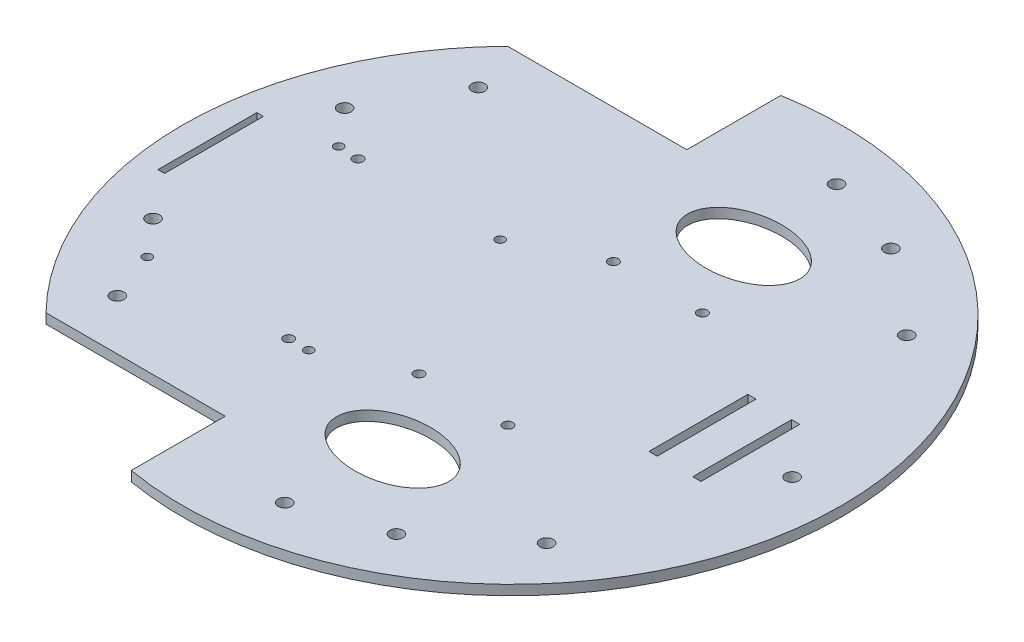
SolidWorks part; units mm, degrees
ref_plane "Спереди" through (0, 0, 0) normal (0, 0, 1) x (1, 0, 0)
ref_plane "Сверху" through (0, 0, 0) normal (0, 1, 0) x (1, 0, 0)
ref_plane "Справа" through (0, 0, 0) normal (1, 0, 0) x (0, 0, -1)
other "Configuration Table"
sketch "Эскиз1" plane through (0, 0, 0) normal (0, 1, 0) x (1, 0, 0)
  circle A0 centre (0, 0) radius 100
extrude "Бобышка-Вытянуть1" add sketch "Эскиз1" along normal blind 3
sketch "Эскиз2" plane through (0, 3, 0) normal (0, 1, 0) x (1, 0, 0)
  circle A1 centre (85, 0) radius 2
  circle A2 centre (65.1138, -54.6369) radius 2
  circle A3 centre (14.7601, -83.7087) radius 2
  circle A4 centre (-42.5, -73.6122) radius 2
  circle A5 centre (-79.8739, -29.0717) radius 2
  circle A6 centre (-79.8739, 29.0717) radius 2
  circle A7 centre (-42.5, 73.6122) radius 2
  circle A8 centre (14.7601, 83.7087) radius 2
  circle A9 centre (65.1138, 54.6369) radius 2
  point P24 (0, 0)
  dimension "D1" = 9
extrude "Вырез-Вытянуть1" cut sketch "Эскиз2" against normal blind 10
sketch "Эскиз4" plane through (0, 3, 0) normal (0, 1, 0) x (1, 0, 0)
  line L0 (-100, 0) -> (100, 0) construction
  line L1 (-52, -87.543) -> (-52, 90.7524) construction
  line L2 (-87, 70.043) -> (-17, 105.043) construction
  line L3 (-87, -105.043) -> (-17, -105.043)
  line L4 (-87, -105.043) -> (-87, -70.043)
  line L5 (-87, -70.043) -> (-17, -70.043)
  line L6 (-17, -105.043) -> (-17, -70.043)
  line L7 (-87, -105.043) -> (-17, -70.043) construction
  line L8 (-87, -70.043) -> (-17, -105.043) construction
  line L9 (-87, 105.043) -> (-17, 70.043) construction
  line L10 (-17, 105.043) -> (-17, 70.043)
  line L11 (-87, 70.043) -> (-17, 70.043)
  line L12 (-87, 105.043) -> (-87, 70.043)
  line L13 (-87, 105.043) -> (-17, 105.043)
  point P5 (-52, 1.6047)
extrude "Вырез-Вытянуть2" cut sketch "Эскиз4" against normal blind 10
sketch "Эскиз5" plane through (0, 3, 0) normal (0, 1, 0) x (1, 0, 0)
  circle A1 centre (39.9369, -75.0336) radius 2
  circle A2 centre (39.9369, 75.0336) radius 2
  circle A4 centre (-65, 54.7723) radius 2
  circle A5 centre (-65, -54.7723) radius 2
extrude "Вырез-Вытянуть3" cut sketch "Эскиз5" against normal blind 10
sketch "Эскиз6" plane through (0, 0, 0) normal (0, -1, 0) x (1, 0, 0)
  line L3 (-87, -12.5) -> (-90, -12.5)
  line L4 (-87, -12.5) -> (-87, 12.5)
  line L5 (-87, 12.5) -> (-90, 12.5)
  line L6 (-90, -12.5) -> (-90, 12.5)
  line L7 (-87, -12.5) -> (-90, 12.5) construction
  line L8 (-87, 12.5) -> (-90, -12.5) construction
extrude "Бобышка-Вытянуть2" add sketch "Эскиз6" along normal blind 25 contours L6 L5 L4 L3
sketch "Эскиз7" plane through (-90, 0, 0) normal (-1, 0, 0) x (0, 0, 1)
  circle A0 centre (-10, -22.5) radius 1
  circle A1 centre (10, -22.5) radius 1
  circle A2 centre (-10, -8.5) radius 1
  circle A3 centre (10, -8.5) radius 1
  point P0 (0, 0)
extrude "Вырез-Вытянуть4" cut sketch "Эскиз7" against normal blind 30
chamfer "Фаска1" distance 10 angle 45 1 edges at (-88.5, 0, -12.5)
chamfer "Фаска2" distance 10 angle 45 1 edges at (-88.5, 0, 12.5)
chamfer "Фаска3" distance 5 angle 45 1 edges at (-87, 0, 0)
sketch "Эскиз11" plane through (0, 0, 0) normal (0, -1, 0) x (1, 0, 0)
  line L0 (-90, -14.5615) -> (-90, 15.4385)
  line L1 (-90, -22.5) -> (-90, 22.5) construction
  line L3 (-90, 15.4385) -> (-92, 15.4385)
  line L5 (-90, -14.5615) -> (-92, -14.5615)
  line L6 (-92, 15.4385) -> (-92, -14.5615)
extrude "Вырез-Вытянуть5" cut sketch "Эскиз11" against normal blind 30
sketch "Эскиз12" plane through (0, 0, 0) normal (0, -1, 0) x (1, 0, 0)
  line L0 (14.7601, 83.7087) -> (14.7601, -83.7087) construction
  line L1 (28.2601, -29.5) -> (1.2601, 29.5) construction
  line L2 (1.2601, -29.5) -> (28.2601, 29.5) construction
  line L3 (14.7601, 0) -> (-82, 0) construction
  line L5 (-82, 22.5) -> (-82, -22.5) construction
  circle A0 centre (1.2601, -29.5) radius 1.5
  circle A1 centre (1.2601, 29.5) radius 1.5
  circle A2 centre (28.2601, -29.5) radius 1.5
  circle A3 centre (28.2601, 29.5) radius 1.5
  circle A16 centre (-70.6889, 40) radius 1.3645
  circle A17 centre (-27.7378, 40.0327) radius 1.5
  circle A18 centre (-21.6889, 40) radius 1.3645
  circle A19 centre (-21.6889, -18.0855) radius 1.3645
  circle A20 centre (-64.4898, -17.737) radius 1.5
  circle A21 centre (-70.6889, -18.0855) radius 1.3645
extrude "Вырез-Вытянуть6" cut sketch "Эскиз12" against normal blind 10
sketch "Эскиз13" plane through (0, 0, 0) normal (0, -1, 0) x (1, 0, 0)
  line L0 (0, 0) -> (100, 0) construction
  line L1 (69.8255, -15) -> (72.3255, 15) construction
  line L2 (56.5444, -15) -> (59.0444, -15)
  line L3 (56.5444, -15) -> (56.5444, 15)
  line L4 (56.5444, 15) -> (59.0444, 15)
  line L5 (59.0444, -15) -> (59.0444, 15)
  line L6 (56.5444, -15) -> (59.0444, 15) construction
  line L7 (56.5444, 15) -> (59.0444, -15) construction
  line L8 (69.8255, 15) -> (72.3255, 15)
  line L9 (69.8255, -15) -> (72.3255, -15)
  line L10 (72.3255, -15) -> (72.3255, 15)
  line L11 (69.8255, 15) -> (72.3255, -15) construction
  line L12 (69.8255, -15) -> (69.8255, 15)
  arc A0 (-17, -98.5444) -> (-17, 98.5444) centre (0, 0) ccw construction
  point P6 (57.7944, 0)
  point P11 (71.0755, 0)
extrude "Вырез-Вытянуть7" cut sketch "Эскиз13" against normal blind 10
sketch "Эскиз14" plane through (0, 0, 0) normal (0, -1, 0) x (1, 0, 0)
  ellipse E0 centre (17.0454, 53.2667) end of major axis (0, 53.2667) minor radius 11.4524
  ellipse E1 centre (17.0454, -53.2667) end of major axis (0, -53.2667) minor radius 11.4524
extrude "Вырез-Вытянуть8" cut sketch "Эскиз14" against normal blind 10
